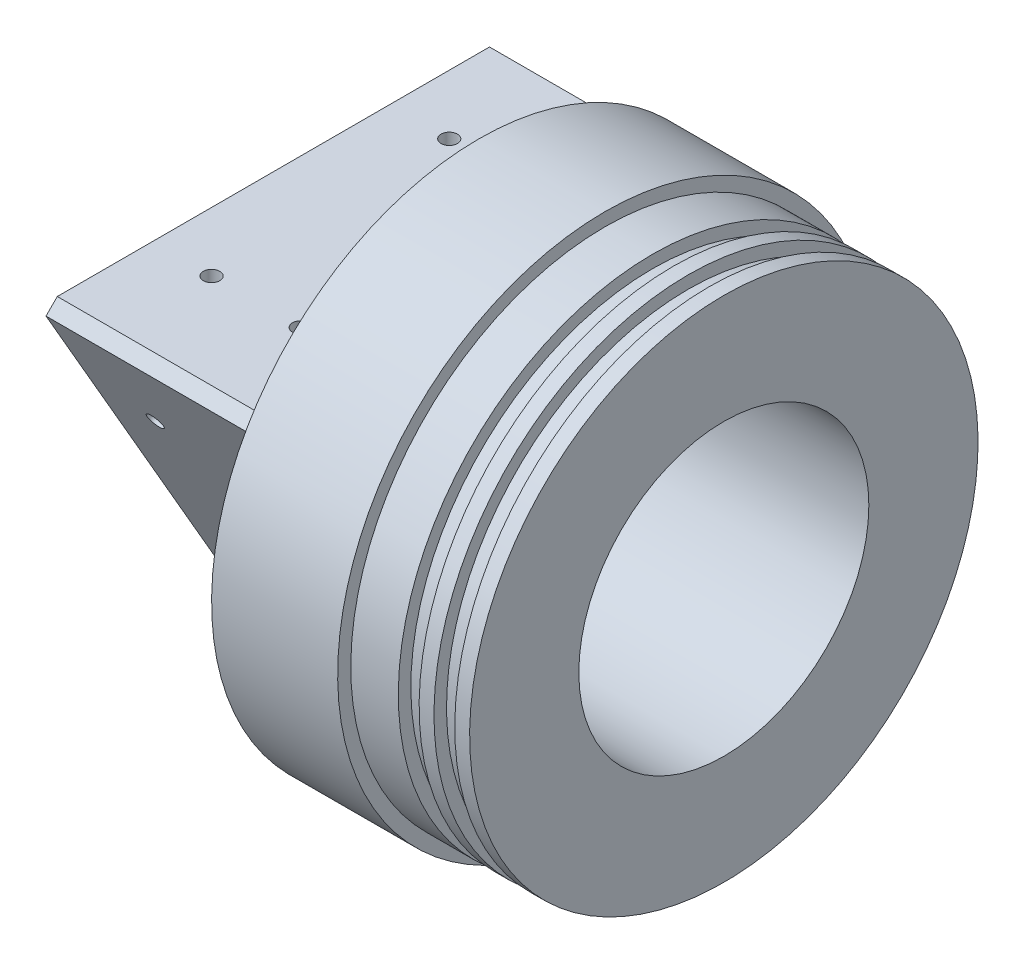
SolidWorks part; units mm, degrees
ref_plane "Frontal Plane" through (0, 0, 0) normal (0, 0, 1) x (1, 0, 0)
ref_plane "Horizontal Plane" through (0, 0, 0) normal (0, 1, 0) x (1, 0, 0)
ref_plane "Profile Plane" through (0, 0, 0) normal (1, 0, 0) x (0, 0, -1)
sketch "Sketch1" plane through (0, 0, 0) normal (1, 0, 0) x (0, 0, -1)
  line L0 (-49.4934, 28.575) -> (49.4934, 28.575)
  line L1 (49.4934, 28.575) -> (0, -57.15)
  line L2 (0, -57.15) -> (-49.4934, 28.575)
  circle A0 centre (0, 0) radius 57.15 construction
  dimension "D1" = 114.3
extrude "Boss-Extrude1" add sketch "Sketch1" along normal mid plane 44.45
sketch "Sketch4" plane through (-22.225, 0, 0) normal (-1, 0, 0) x (0, 0, 1)
  circle A0 centre (0, 0) radius 22.5
  dimension "D1" = 45
extrude "Cut-Extrude2" cut sketch "Sketch4" against normal blind 39
chamfer "Chamfer1" distance 1.27 angle 30 1 edges at (-22.225, 0, 22.5)
sketch "Sketch5" plane through (0, 0, 0) normal (1, 0, 0) x (0, 0, -1)
  circle A0 centre (0, 0) radius 20
  dimension "D1" = 40
extrude "Cut-Extrude3" cut sketch "Sketch5" along normal up to surface (22.225 mm away) up to face at (22.225, 0, 0)
sketch "Sketch6" plane through (0, 0, 0) normal (0, 0, 1) x (1, 0, 0)
  line L0 (0, 0) -> (22.225, 0)
  line L1 (22.225, 28.575) -> (22.225, -57.15) construction
  line L2 (22.225, 0) -> (22.225, 57.15)
  line L3 (22.225, 57.15) -> (49.175, 57.15)
  line L4 (49.175, 57.15) -> (49.175, 54.3433)
  line L5 (49.175, 54.3433) -> (59.335, 54.3433)
  line L6 (59.335, 54.3433) -> (59.335, 51.6636)
  line L7 (59.335, 51.6636) -> (63.78, 51.6636)
  line L8 (63.78, 51.6636) -> (63.78, 54.3433)
  line L9 (63.78, 54.3433) -> (66.955, 54.3433)
  line L10 (66.955, 54.3433) -> (66.955, 51.6636)
  line L11 (66.955, 51.6636) -> (71.4, 51.6636)
  line L12 (71.4, 51.6636) -> (71.4, 54.3433)
  line L13 (71.4, 54.3433) -> (74.575, 54.3433)
  line L14 (74.575, 54.3433) -> (74.575, 0)
  line L15 (74.575, 0) -> (22.225, 0)
  point P11 (64.2026, 31.2531)
  point P20 (63.8903, 33.5434)
  dimension "D1" = 26.95
  dimension "D2" = 25.4
  dimension "D3" = 10.16
  dimension "D4" = 4.445
  dimension "D5" = 54.3433
  dimension "D6" = 57.15
  dimension "D7" = 51.6636
revolve "Revolve1" add sketch "Sketch6" angle 360 about L15
hole_wizard "#6-32 Tapped Hole2" positions "Sketch7" profile "Sketch8" tap size "#6-32" standard "ANSI Inch"
sketch "Sketch7" plane through (0, 28.575, 0) normal (0, 1, 0) x (1, 0, 0)
  line L1 (9.525, 25.4) -> (-9.525, 25.4) construction
  line L2 (-9.525, 25.4) -> (-9.525, -25.4) construction
  line L3 (-9.525, -25.4) -> (9.525, -25.4) construction
  line L4 (9.525, -25.4) -> (9.525, 25.4) construction
  point P0 (-9.525, 25.4)
  point P2 (9.525, 25.4)
  point P4 (9.525, -25.4)
  point P6 (-9.525, -25.4)
  point P33 (0, 25.4)
  point P34 (-9.525, 0)
  dimension "D1" = 50.8
  dimension "D3" = 19.05
sketch "Sketch8" plane through (-9.525, 28.575, -25.4) normal (1, 0, 0) x (0, 0, 1)
  line L0 (0, 0) -> (0, 13.5127)
  line L1 (0, 13.5127) -> (1.3525, 12.7)
  line L2 (1.3525, 12.7) -> (1.3525, 5.588)
  line L3 (1.3525, 5.588) -> (1.7526, 5.588)
  line L4 (1.7526, 5.588) -> (1.7526, 0)
  line L5 (1.7526, 0) -> (0, 0)
  line L10 (0, 13.5127) -> (-1.3526, 12.7) construction
  line L11 (0, -6.35) -> (0, 107.95) construction
  dimension "Tap Drill Dia." = 2.7051
  dimension "Tap Drill Depth" = 12.7
  dimension "Thread Major Dia." = 3.5052
  dimension "Thread Depth" = 5.588
  dimension "Drill Angle" = 118
pattern_circular "CirPattern1" count 3 over 360 about axis through (0, 0, 0) along (1, 0, 0) of "#6-32 Tapped Hole2"
sketch "Sketch9" plane through (74.575, 0, 0) normal (1, 0, 0) x (0, 0, -1)
  circle A0 centre (0, 0) radius 31
  dimension "D1" = 62
extrude "Cut-Extrude5" cut sketch "Sketch9" against normal blind 46
sketch "Sketch10" plane through (28.575, 0, 0) normal (1, 0, 0) x (0, 0, -1)
  circle A0 centre (0, 0) radius 17.5
  dimension "D1" = 35
extrude "Cut-Extrude6" cut sketch "Sketch10" against normal up to next
chamfer "Chamfer2" distance 3.81 angle 45 3 edges at (0, -57.15, 0) (0, 28.575, -49.4934) (0, 28.575, 49.4934)
fillet "Fillet4" radius 1.27 6 edges at (22.225, 26.9252, -47.1463) (22.225, -14.7296, -24.4915) (22.225, -54.2925, 0.2552) (22.225, -13.8454, 25.0019) (22.225, 27.3673, 46.8911) (22.225, 28.575, -0.5104)
